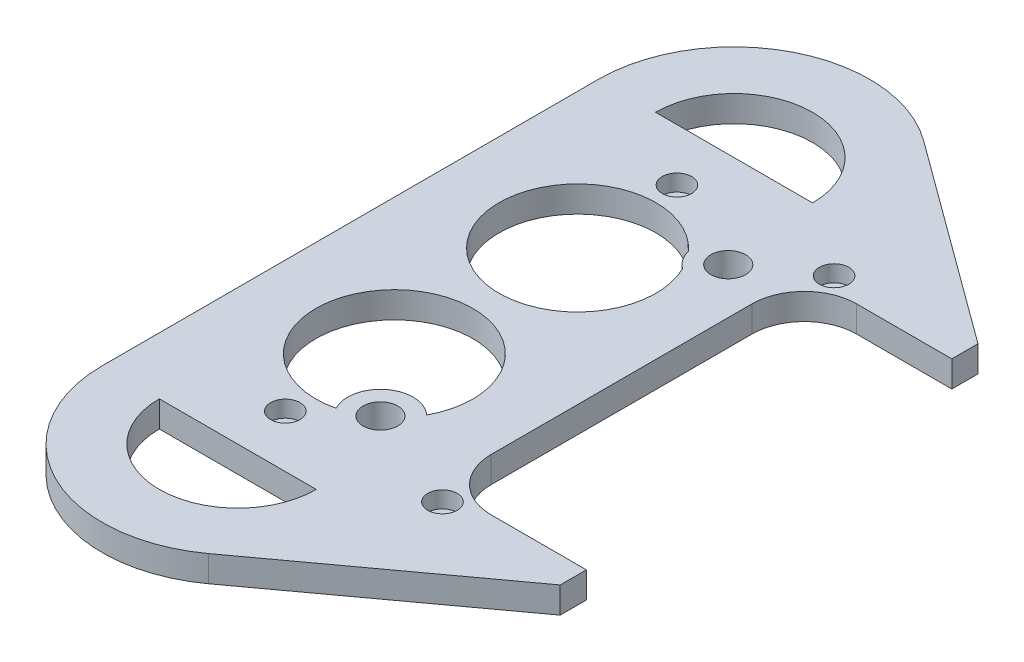
SolidWorks part; units mm, degrees
ref_plane "Front Plane" through (0, 0, 0) normal (0, 0, 1) x (1, 0, 0)
ref_plane "Top Plane" through (0, 0, 0) normal (0, 1, 0) x (1, 0, 0)
ref_plane "Right Plane" through (0, 0, 0) normal (1, 0, 0) x (0, 0, -1)
sketch "Sketch1" plane through (0, 53.2785, 0) normal (0, 1, 0) x (1, 0, 0)
  line L0 (-60.9331, 0) -> (34.3543, 0) construction
  line L1 (34.3543, 101.3894) -> (-60.9331, 101.3894) construction
  line L2 (-60.9331, 0) -> (34.3543, 0)
  line L3 (34.3543, 101.3894) -> (-1.4507, 101.3894)
  line L4 (-34.3669, 110.9144) -> (-34.3669, -9.525) construction
  line L5 (-1.4507, 110.9144) -> (-1.4507, -9.525)
  line L6 (-67.2831, 110.9144) -> (-67.2831, -9.525)
  line L7 (34.3543, 0) -> (34.3543, 6.35) construction
  line L8 (34.3543, 101.3894) -> (34.3543, 95.0394) construction
  line L9 (34.3543, 0) -> (34.3543, 6.35)
  line L10 (34.3543, 101.3894) -> (34.3543, 95.0394)
  line L11 (34.3543, 101.3894) -> (-14.9198, 137.4716)
  line L12 (34.3543, 95.0394) -> (-60.9331, 95.0394) construction
  line L13 (-60.9331, 6.35) -> (34.3543, 6.35) construction
  line L14 (34.3543, 95.0394) -> (-1.4507, 95.0394)
  line L15 (-1.4507, 6.35) -> (34.3543, 6.35)
  line L16 (-1.4507, 101.3894) -> (-60.9331, 101.3894)
  line L17 (34.3543, 0) -> (-14.9198, -36.0822)
  line L20 (-15.3169, 110.9144) -> (-53.4169, 110.9144)
  line L21 (-15.3169, -9.525) -> (-53.4169, -9.525)
  line L22 (-15.3169, 110.9144) -> (-15.3169, -9.525) construction
  line L23 (-53.4169, 110.9144) -> (-53.4169, -9.525) construction
  line L25 (-34.3669, 28.4697) -> (-34.3669, -9.525) construction
  line L27 (-34.3669, 72.9197) -> (-34.3669, 110.9144) construction
  arc A0 (-1.4507, 110.9144) -> (-67.2831, 110.9144) centre (-34.3669, 110.9144) ccw
  arc A1 (-67.2831, -9.525) -> (-1.4507, -9.525) centre (-34.3669, -9.525) ccw
  arc A2 (-53.4169, -9.525) -> (-15.3169, -9.525) centre (-34.3669, -9.525) ccw
  arc A3 (-15.3169, 110.9144) -> (-53.4169, 110.9144) centre (-34.3669, 110.9144) ccw
  circle A4 centre (-12.5632, 87.6963) radius 4.572 construction
  circle A6 centre (-12.5632, 87.6963) radius 4.572
  circle A7 centre (-22.9699, 13.6931) radius 4.572
  circle A8 centre (-12.5632, 87.6963) radius 7.9375
  circle A9 centre (-22.9699, 13.6931) radius 7.9375
  circle A10 centre (-34.3669, 28.4697) radius 19.05
  circle A11 centre (-34.3669, 72.9197) radius 19.05
  circle A12 centre (-22.9699, 13.6931) radius 4.572 construction
  point P6 (-34.3669, 50.6947)
  dimension "D5" = 15.875
  dimension "D6" = 38.1
  dimension "D7" = 44.45
  dimension "D2" = 9.525
  dimension "D3" = 9.525
  dimension "D1" = 11.1125
extrude "Boss-Extrude1" add sketch "Sketch1" along normal blind 6.35
fillet "Fillet1" radius 12.7 2 edges at (-1.4507, 56.4535, -95.0394) (-1.4507, 56.4535, -6.35)
hole_wizard "Tap Drill for 3/8-24 Tap1" positions "Sketch2" profile "Sketch3" hole size "3/8-24" standard "ANSI Inch" end condition through all
sketch "Sketch2" plane through (0, 59.6285, 0) normal (0, 1, 0) x (1, 0, 0)
  point P0 (-22.9699, 13.6931)
  point P3 (-12.5632, 87.6963)
sketch "Sketch3" plane through (-22.9699, 59.6285, -13.6931) normal (1, 0, 0) x (0, 0, 1)
  line L0 (0, 0) -> (0, 6.35)
  line L1 (0, 6.35) -> (4.2164, 6.35)
  line L2 (4.2164, 6.35) -> (4.2164, 0)
  line L5 (4.2164, 0) -> (0, 0)
  line L11 (0, -6.35) -> (0, 107.95) construction
  dimension "Thru Hole Dia." = 8.4328
  dimension "Thru Hole Depth" = 6.35
hole_wizard "CBORE for #6 Socket Head Cap Screw1" positions "Sketch4" profile "Sketch5" counterbore size "#6" standard "ANSI Inch" end condition through all
sketch "Sketch4" plane through (0, 59.6285, 0) normal (0, 1, 0) x (1, 0, 0)
  line L0 (34.3543, 101.3894) -> (34.3543, 95.0394) construction
  line L1 (-60.9331, 101.3894) -> (-60.9331, 95.0394) construction
  line L2 (34.3543, 101.3894) -> (34.3543, 95.0394)
  line L3 (-60.9331, 101.3894) -> (-60.9331, 95.0394)
  line L4 (-60.9331, 98.2144) -> (34.3543, 98.2144) construction
  point P0 (2.6043, 3.175)
  point P2 (-35.5331, 3.175)
  point P21 (-35.5331, 98.2144)
  point P23 (2.6043, 98.2144)
sketch "Sketch5" plane through (2.6043, 59.6285, -3.175) normal (1, 0, 0) x (0, 0, 1)
  line L0 (0, 0) -> (0, 6.35)
  line L1 (0, 6.35) -> (1.8986, 6.35)
  line L3 (1.8986, 6.35) -> (1.8986, 4.0132)
  line L4 (1.8986, 4.0132) -> (3.5725, 4.0132)
  line L5 (3.5725, 4.0132) -> (3.5725, 0)
  line L7 (3.5725, 0) -> (0, 0)
  line L11 (0, -6.35) -> (0, 107.95) construction
  dimension "Thru Hole Dia." = 3.7973
  dimension "Thru Hole Depth" = 6.35
  dimension "C'Bore Dia." = 7.145
  dimension "C'Bore Depth" = 4.0132
equation "\"D7@Sketch1\"=\"D6@Sketch1\"+1/4"
equation "\"D2@Sketch1\"=\"D3@Sketch1\""
equation "\"D1@Sketch1\"=\"D5@Sketch1\"/2+1/8"
